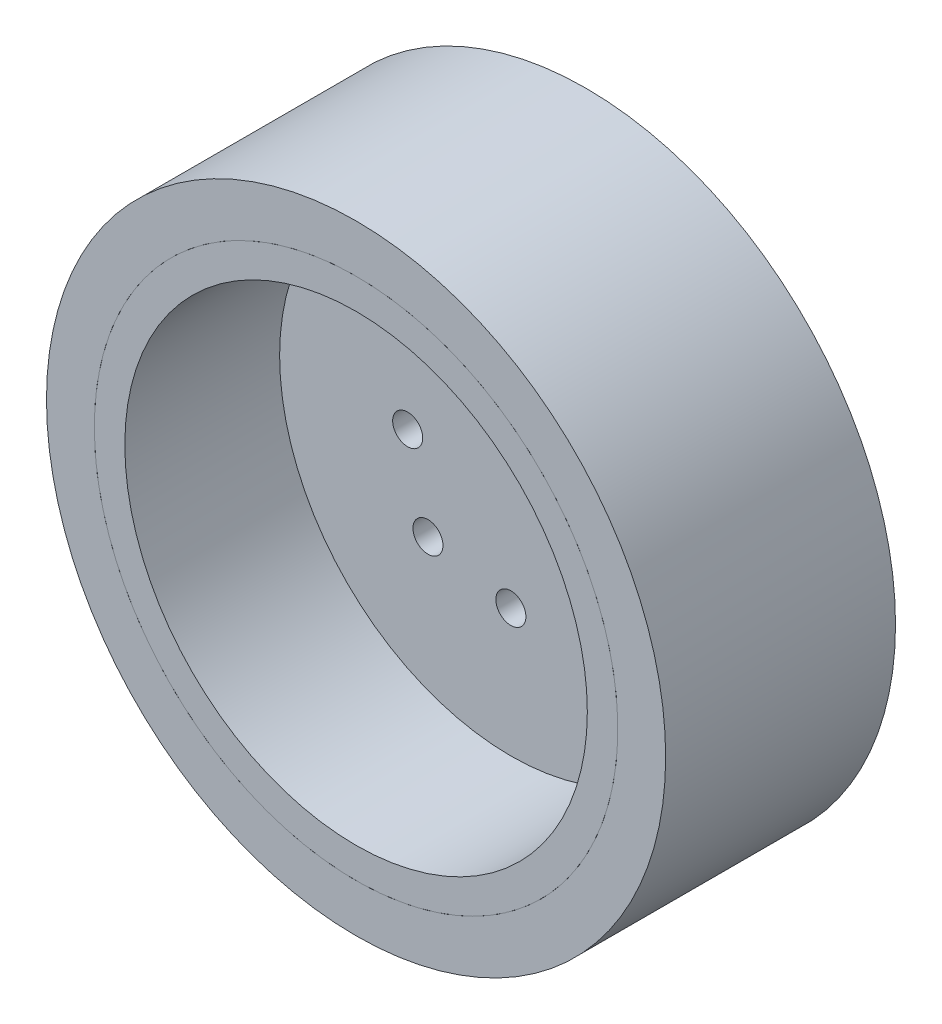
SolidWorks part; units mm, degrees
ref_plane "前视基准面" through (0, 0, 0) normal (0, 0, 1) x (1, 0, 0)
ref_plane "上视基准面" through (0, 0, 0) normal (0, 1, 0) x (1, 0, 0)
ref_plane "右视基准面" through (0, 0, 0) normal (1, 0, 0) x (0, 0, -1)
sketch "草图1" plane through (0, 0, 0) normal (0, 0, 1) x (1, 0, 0)
  circle A0 centre (0, 0) radius 26.4
  dimension "D1" = 52.8
extrude "凸台-拉伸1" add sketch "草图1" along normal blind 24.5
sketch "草图2" plane through (0, 0, 24.5) normal (0, 0, 1) x (1, 0, 0)
  circle A0 centre (0, 0) radius 24.65
  dimension "D1" = 49.3
extrude "切除-拉伸1" cut sketch "草图2" against normal offset from surface (16.5 mm away) 8 up to face at (26.4, 0, 0)
sketch "草图5" plane through (0, 0, 24.5) normal (0, 0, 1) x (1, 0, 0)
  circle A1 centre (0, 0) radius 26.4 construction
  circle A2 centre (0, 0) radius 26.4
  circle A5 centre (0, 0) radius 27.9
  circle A6 centre (0, 0) radius 27.9
  dimension "D1" = 1.5
extrude "凸台-拉伸3" add sketch "草图5" against normal blind 1.5
ref_plane "基准面1" through (0, 0, 12.25) normal (0, 0, -1) x (-1, 0, 0)
mirror "镜向1" about plane through (0, 0, 12.25) normal (0, 0, -1) of "凸台-拉伸3"
sketch "草图4" plane through (0, 0, 0) normal (0, 0, -1) x (-1, 0, 0)
  line L0 (-8.8388, -8.8388) -> (8.8388, -8.8388) construction
  line L1 (-8.8388, -8.8388) -> (-8.8388, 8.8388) construction
  line L2 (-8.8388, 8.8388) -> (8.8388, 8.8388) construction
  line L3 (8.8388, -8.8388) -> (8.8388, 8.8388) construction
  line L4 (0, 8.8388) -> (0, -8.8388) construction
  line L5 (-8.8388, 0) -> (8.8388, 0) construction
  circle A5 centre (0, 0) radius 11 construction
  circle A6 centre (0, 11) radius 1.6
  circle A7 centre (11, 0) radius 1.6
  circle A8 centre (0, -11) radius 1.6
  circle A9 centre (-11, 0) radius 1.6
  circle A10 centre (8.8388, 8.8388) radius 1.6
  circle A11 centre (-8.8388, 8.8388) radius 1.6
  circle A12 centre (-8.8388, -8.8388) radius 1.6
  circle A13 centre (8.8388, -8.8388) radius 1.6
  point P14 (0, 0)
  dimension "D1" = 22
  dimension "D2" = 3.2
  dimension "D3" = 12.5
extrude "切除-拉伸2" cut sketch "草图4" against normal through all
sketch "草图6" plane through (0, 0, 0) normal (0, 1, 0) x (1, 0, 0)
  line L0 (-33, 0) -> (-33, -24.5)
  line L1 (-33, -24.5) -> (-27.9, -24.5)
  line L3 (-27.9, 0) -> (-27.9, -1.5) construction
  line L4 (-27.9, -1.5) -> (27.9, -1.5) construction
  line L5 (27.9, -23) -> (-27.9, -23) construction
  line L6 (-26.4, -1.5) -> (-26.4, -23) construction
  line L8 (-27.9, 0) -> (-27.9, -1.5)
  line L9 (-27.9, -1.5) -> (-26.4, -1.5)
  line L10 (-26.4, -23) -> (-27.9, -23)
  line L11 (-26.4, -1.5) -> (-26.4, -23)
  line L13 (-33, 0) -> (-27.9, 0)
  line L14 (-27.9, -23) -> (-27.9, -24.5) construction
  line L15 (-27.9, -23) -> (-27.9, -24.5)
  line L16 (0, 0.3384) -> (0, -49999.6616) construction
  dimension "D1" = 33
revolve "旋转1" add sketch "草图6" angle 360 about L16
